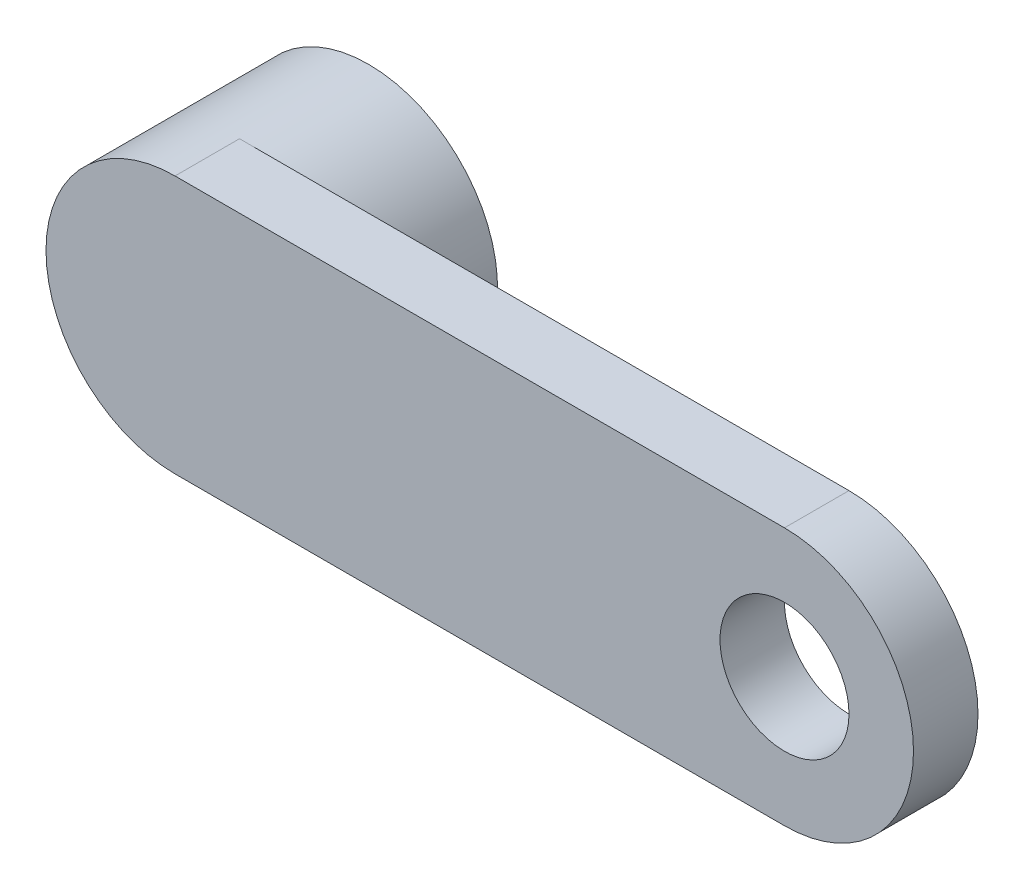
SolidWorks part; units mm, degrees
ref_plane "Front" through (0, 0, 0) normal (0, 0, 1) x (1, 0, 0)
ref_plane "Top" through (0, 0, 0) normal (0, 1, 0) x (1, 0, 0)
ref_plane "Right" through (0, 0, 0) normal (1, 0, 0) x (0, 0, -1)
sketch "Sketch1" plane through (0, 0, 0) normal (0, 0, 1) x (1, 0, 0)
  line L0 (0, 0) -> (15, 0) construction
  line L1 (0, 3.175) -> (15, 3.175)
  line L2 (0, -3.175) -> (15, -3.175)
  arc A0 (0, 3.175) -> (0, -3.175) centre (0, 0) ccw
  arc A1 (15, -3.175) -> (15, 3.175) centre (15, 0) ccw
  circle A2 centre (15, 0) radius 1.5875
  point P4 (7.5, 0)
  dimension "D1" = 3.175
  dimension "D2" = 6.35
extrude "Boss-Extrude1" add sketch "Sketch1" against normal blind 1.5875
sketch "Sketch2" plane through (0, 0, -1.5875) normal (0, 0, -1) x (-1, 0, 0)
  circle A0 centre (0, 0) radius 3.175
  circle A1 centre (0, 0) radius 1.5875
  arc A2 (0, -3.175) -> (0, 3.175) centre (0, 0) ccw construction
  dimension "D1" = 3.175
extrude "Boss-Extrude2" add sketch "Sketch2" along normal blind 3.175
